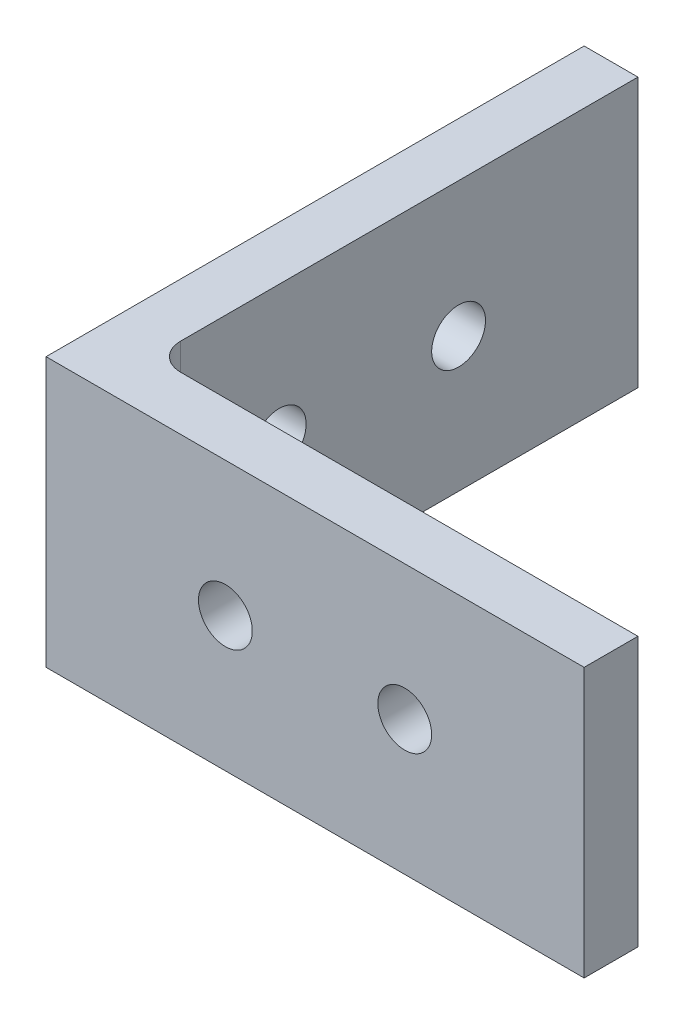
SolidWorks part; units mm, degrees
material "6061 Alloy"
ref_plane "Front Plane" through (0, 0, 0) normal (0, 0, 1) x (1, 0, 0)
ref_plane "Top Plane" through (0, 0, 0) normal (0, 1, 0) x (1, 0, 0)
ref_plane "Right Plane" through (0, 0, 0) normal (1, 0, 0) x (0, 0, -1)
sketch "Sketch1" plane through (0, 0, 0) normal (0, 1, 0) x (1, 0, 0)
  line L0 (0, 0) -> (0, 100)
  line L1 (0, 100) -> (10, 100)
  line L2 (10, 100) -> (10, 10)
  line L3 (10, 10) -> (100, 10)
  line L4 (100, 10) -> (100, 0)
  line L5 (100, 0) -> (0, 0)
  dimension "D1" = 100
  dimension "D2" = 100
  dimension "D3" = 10
  dimension "D4" = 10
extrude "Boss-Extrude1" add sketch "Sketch1" along normal mid plane 50
fillet "Fillet1" radius 5 1 edges at (10, 0, -10)
sketch "Sketch2" plane through (10, 0, 0) normal (1, 0, 0) x (0, 0, -1)
  line L0 (0, 25) -> (0, -25) construction
  line L2 (15, 25) -> (100, 25) construction
  circle A0 centre (33.333, 0) radius 5
  circle A1 centre (66.666, 0) radius 5
  point P8 (0, 0)
  dimension "D2" = 10
  dimension "D3" = 33.333
  dimension "D4" = 33.333
  dimension "D5" = 25
extrude "Cut-Extrude1" cut sketch "Sketch2" against normal through all
sketch "Sketch3" plane through (0, 0, -10) normal (0, 0, -1) x (-1, 0, 0)
  line L1 (-100, 25) -> (-100, -25) construction
  circle A0 centre (-33.33, 0) radius 5
  circle A1 centre (-66.66, 0) radius 5
  dimension "D1" = 10
  dimension "D2" = 33.34
  dimension "D3" = 33.33
extrude "Cut-Extrude2" cut sketch "Sketch3" against normal through all
